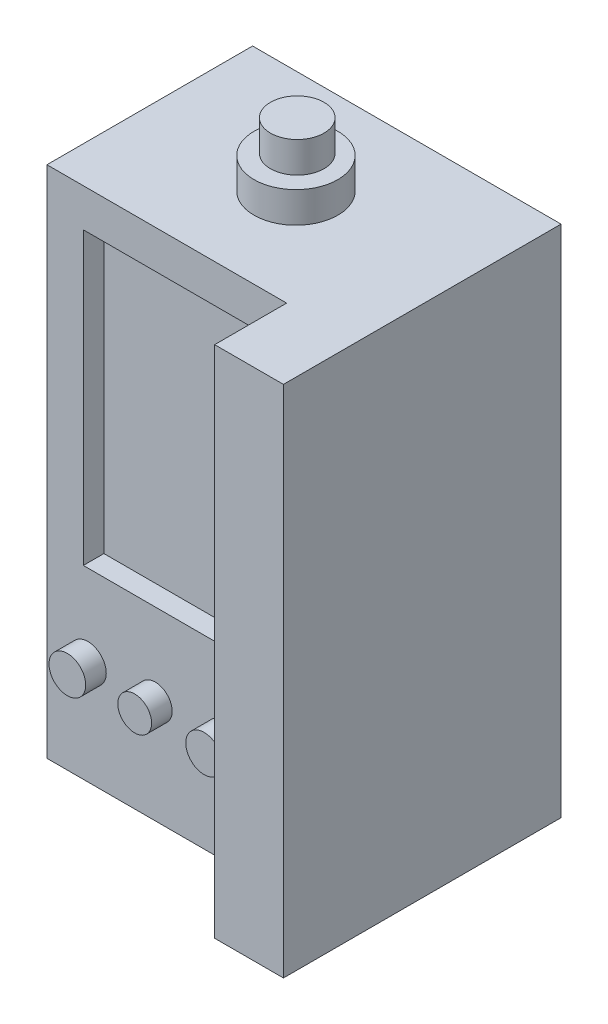
SolidWorks part; units mm, degrees
ref_plane "Front Plane" through (0, 0, 0) normal (0, 0, 1) x (1, 0, 0)
ref_plane "Top Plane" through (0, 0, 0) normal (0, 1, 0) x (1, 0, 0)
ref_plane "Right Plane" through (0, 0, 0) normal (1, 0, 0) x (0, 0, -1)
sketch "Sketch1" plane through (0, 0, 0) normal (0, 0, 1) x (1, 0, 0)
  line L1 (-28.5756, 41.0776) -> (1.4244, 41.0776)
  line L2 (-28.5756, 41.0776) -> (-28.5756, -8.9224)
  line L3 (-28.5756, -8.9224) -> (1.4244, -8.9224)
  line L4 (1.4244, 41.0776) -> (1.4244, -8.9224)
  line L5 (-28.5756, 41.0776) -> (1.4244, -8.9224) construction
  line L6 (-28.5756, -8.9224) -> (1.4244, 41.0776) construction
  point P0 (-13.5756, 16.0776)
  dimension "D1" = 30
  dimension "D2" = 50
extrude "Boss-Extrude1" add sketch "Sketch1" along normal blind 20
sketch "Sketch2" plane through (0, 0, 20) normal (0, 0, 1) x (1, 0, 0)
  line L1 (-25.0376, 37.3672) -> (-7.4475, 37.3672)
  line L2 (-25.0376, 37.3672) -> (-25.0376, 9.0952)
  line L3 (-25.0376, 9.0952) -> (-7.4475, 9.0952)
  line L4 (-7.4475, 37.3672) -> (-7.4475, 9.0952)
  line L5 (-25.0376, 37.3672) -> (-7.4475, 9.0952) construction
  line L6 (-25.0376, 9.0952) -> (-7.4475, 37.3672) construction
  point P0 (-16.2426, 23.2312)
extrude "Cut-Extrude1" cut sketch "Sketch2" against normal blind 2
sketch "Sketch3" plane through (0, 0, 20) normal (0, 0, 1) x (1, 0, 0)
  line L0 (-5.2664, 41.0776) -> (-5.2664, -8.9224)
  line L1 (1.4244, 41.0776) -> (-28.5756, 41.0776) construction
  line L2 (-28.5756, -8.9224) -> (1.4244, -8.9224) construction
  line L3 (-5.2664, -8.9224) -> (1.4244, -8.9224)
  line L4 (1.4244, -8.9224) -> (1.4244, 41.0776)
  line L5 (1.4244, -8.9224) -> (1.4244, 41.0776) construction
  line L6 (1.4244, 41.0776) -> (-4.5487, 41.0776)
  line L7 (1.4244, 41.0776) -> (-4.5487, 41.0776)
  line L11 (1.4244, -8.9224) -> (1.4244, 41.0776)
  line L12 (1.4244, 41.0776) -> (-28.5756, 41.0776)
  line L13 (-28.5756, 41.0776) -> (-28.5756, -8.9224)
  line L14 (-28.5756, -8.9224) -> (1.4244, -8.9224)
  line L15 (1.4244, -8.9224) -> (1.4244, 41.0776)
  line L16 (-5.2664, 41.0776) -> (-28.5756, 41.0776)
  line L17 (-28.5756, 41.0776) -> (-28.5756, -8.9224)
  line L18 (-28.5756, -8.9224) -> (1.4244, -8.9224)
  line M9 (1.4244, -8.9224) -> (1.4244, 41.0776)
  line M10 (1.4244, 41.0776) -> (-28.5756, 41.0776)
  line M12 (-28.5756, -8.9224) -> (1.4244, -8.9224)
  dimension "D1" = 0
extrude "Boss-Extrude2" add sketch "Sketch3" along normal blind 7 contours L0 M10 M12 M9
sketch "Sketch4" plane through (0, 0, 20) normal (0, 0, 1) x (1, 0, 0)
  circle A0 centre (-24.5913, 1.1289) radius 1.7834
  circle A1 centre (-18.0416, 1.1289) radius 1.6442
  circle A2 centre (-11.2917, 1.1289) radius 1.7818
extrude "Boss-Extrude3" add sketch "Sketch4" along normal blind 2
sketch "Sketch5" plane through (0, 41.0776, 0) normal (0, 1, 0) x (1, 0, 0)
  circle A0 centre (-14.2494, -10.1102) radius 4.0744
extrude "Boss-Extrude4" add sketch "Sketch5" along normal blind 3
sketch "Sketch6" plane through (0, 44.0776, 0) normal (0, 1, 0) x (1, 0, 0)
  circle A0 centre (-14.3649, -9.868) radius 2.6017
extrude "Boss-Extrude5" add sketch "Sketch6" along normal blind 3
scale "Scale1" scale about centroid uniform scaling yes scale factor 0.7
